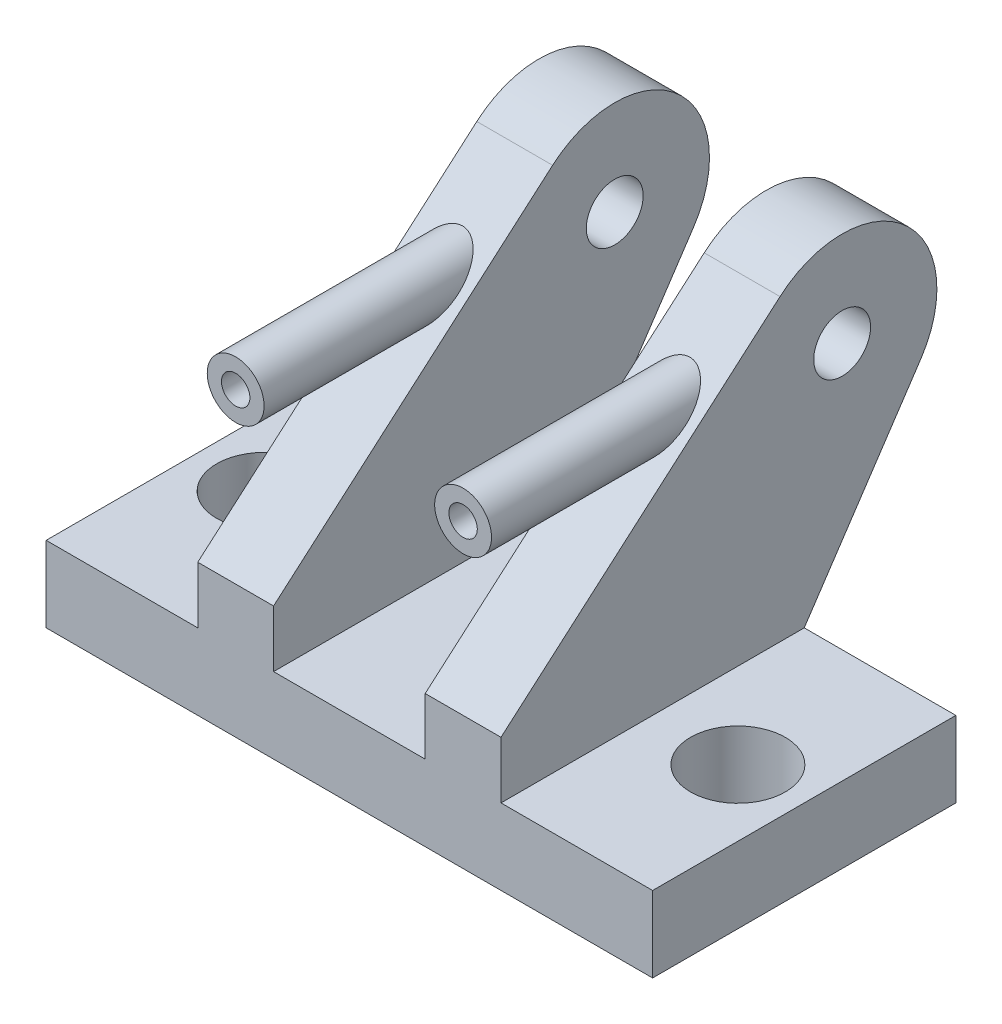
SolidWorks part; units mm, degrees
ref_plane "前视基准面" through (0, 0, 0) normal (0, 0, 1) x (1, 0, 0)
ref_plane "上视基准面" through (0, 0, 0) normal (0, 1, 0) x (1, 0, 0)
ref_plane "右视基准面" through (0, 0, 0) normal (1, 0, 0) x (0, 0, -1)
other "Configuration Table"
sketch "草图1" plane through (0, 0, 0) normal (0, 1, 0) x (1, 0, 0)
  line L1 (-32, 16) -> (32, 16)
  line L2 (-32, 16) -> (-32, -16)
  line L3 (-32, -16) -> (32, -16)
  line L4 (32, 16) -> (32, -16)
  line L5 (-32, 16) -> (32, -16) construction
  line L6 (-32, -16) -> (32, 16) construction
  point P0 (0, 0)
  point P5 (0, 0)
  dimension "D1" = 64
  dimension "D2" = 32
extrude "凸台-拉伸1" add sketch "草图1" along normal blind 8
sketch "草图2" plane through (0, 0, 0) normal (1, 0, 0) x (0, 0, -1)
  line L0 (-16, 8) -> (-16, 14)
  line L1 (-16, 14) -> (13.4459, 39.5527)
  line L2 (28.3167, 26.4472) -> (16, 8)
  line L3 (16, 8) -> (-16, 8)
  arc A0 (13.4459, 39.5527) -> (28.3167, 26.4472) centre (20, 32) cw
  circle A1 centre (20, 32) radius 3
  dimension "D1" = 14
  dimension "D3" = 10
  dimension "D5" = 6
  dimension "D2" = 32
  dimension "D4" = 36
extrude "凸台-拉伸2" add sketch "草图2" along normal blind 8 from offset 8
sketch "草图3" plane through (0, 0, 16) normal (0, 0, 1) x (1, 0, 0)
  line L1 (16, 14) -> (8, 14) construction
  circle A1 centre (12, 31.7704) radius 3
  point P4 (12, 14)
  dimension "D1" = 6
extrude "凸台-拉伸3" add sketch "草图3" against normal up to surface (20.4779 mm away) contours A1
sketch "草图4" plane through (0, 0, 16) normal (0, 0, 1) x (1, 0, 0)
  circle A0 centre (12, 31.7704) radius 1.5
  dimension "D1" = 3
extrude "切除-拉伸1" cut sketch "草图4" against normal up to next
mirror "镜向1" about plane through (0, 0, 0) normal (1, 0, 0) of "切除-拉伸1", "凸台-拉伸3", "凸台-拉伸2"
sketch "草图5" plane through (0, 0, 0) normal (0, 1, 0) x (1, 0, 0)
  line L2 (-32, 16) -> (-32, -16) construction
  circle A0 centre (-25, 0) radius 5
  dimension "D1" = 7
extrude "切除-拉伸3" cut sketch "草图5" against normal blind 8 and the other way through all
mirror "镜向2" about plane through (0, 0, 0) normal (1, 0, 0) of "切除-拉伸3"
